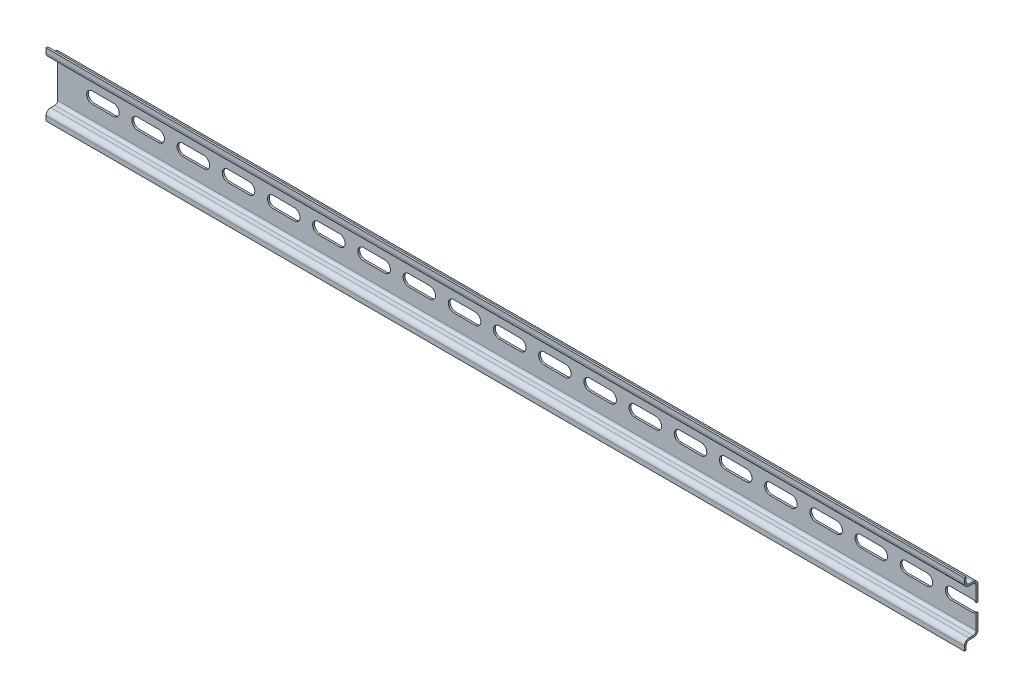
SolidWorks part; units mm, degrees
ref_plane "Front Plane" through (0, 0, 0) normal (0, 0, 1) x (1, 0, 0)
ref_plane "Top Plane" through (0, 0, 0) normal (0, 1, 0) x (1, 0, 0)
ref_plane "Right Plane" through (0, 0, 0) normal (1, 0, 0) x (0, 0, -1)
sketch "Sketch1" plane through (0, 0, 0) normal (1, 0, 0) x (0, 0, -1)
  line L0 (0, 0) -> (96.2341, 0) construction
  line L1 (0, 12.446) -> (0, -12.446)
  line L2 (0, -12.446) -> (-6.484, -12.446)
  line L3 (-6.484, -12.446) -> (-6.484, -17.526)
  line L4 (-6.484, -17.526) -> (-5.484, -17.526)
  line L5 (-5.484, -17.526) -> (-5.484, -13.462)
  line L6 (-5.484, -13.462) -> (1.016, -13.462)
  line L9 (1.016, -13.462) -> (1.016, 13.462)
  line L10 (-5.484, 17.526) -> (-5.484, 13.462)
  line L11 (-6.484, 17.526) -> (-5.484, 17.526)
  line L12 (-6.484, 12.446) -> (-6.484, 17.526)
  line L13 (0, 12.446) -> (-6.484, 12.446)
  line L14 (-5.484, 13.462) -> (1.016, 13.462)
  point P20 (1.016, 0)
  dimension "D1" = 96.2341
  dimension "D2" = 26.924
  dimension "D3" = 7.5
  dimension "D4" = 1
  dimension "D5" = 1.016
  dimension "D8" = 1.016
  dimension "D9" = 35.052
extrude "Boss-Extrude1" add sketch "Sketch1" along normal blind 1000
sketch "Sketch2" plane through (0, 0, -1.016) normal (0, 0, -1) x (-1, 0, 0)
  line L0 (-980.825, 0) -> (-969.175, 0) construction
  line L1 (-980.825, 3.175) -> (-969.175, 3.175)
  line L2 (-980.825, -3.175) -> (-969.175, -3.175)
  line L3 (-1000, -13.462) -> (-1000, 13.462) construction
  line L4 (-955.825, 0) -> (-944.175, 0) construction
  line L5 (-955.825, 3.175) -> (-944.175, 3.175)
  line L6 (-955.825, -3.175) -> (-944.175, -3.175)
  line L7 (-930.825, 0) -> (-919.175, 0) construction
  line L8 (-930.825, 3.175) -> (-919.175, 3.175)
  line L9 (-930.825, -3.175) -> (-919.175, -3.175)
  line L10 (-905.825, 0) -> (-894.175, 0) construction
  line L11 (-905.825, 3.175) -> (-894.175, 3.175)
  line L12 (-905.825, -3.175) -> (-894.175, -3.175)
  line L13 (-880.825, 0) -> (-869.175, 0) construction
  line L14 (-880.825, 3.175) -> (-869.175, 3.175)
  line L15 (-880.825, -3.175) -> (-869.175, -3.175)
  line L16 (-855.825, 0) -> (-844.175, 0) construction
  line L17 (-855.825, 3.175) -> (-844.175, 3.175)
  line L18 (-855.825, -3.175) -> (-844.175, -3.175)
  line L19 (-830.825, 0) -> (-819.175, 0) construction
  line L20 (-830.825, 3.175) -> (-819.175, 3.175)
  line L21 (-830.825, -3.175) -> (-819.175, -3.175)
  line L22 (-805.825, 0) -> (-794.175, 0) construction
  line L23 (-805.825, 3.175) -> (-794.175, 3.175)
  line L24 (-805.825, -3.175) -> (-794.175, -3.175)
  line L25 (-780.825, 0) -> (-769.175, 0) construction
  line L26 (-780.825, 3.175) -> (-769.175, 3.175)
  line L27 (-780.825, -3.175) -> (-769.175, -3.175)
  line L28 (-755.825, 0) -> (-744.175, 0) construction
  line L29 (-755.825, 3.175) -> (-744.175, 3.175)
  line L30 (-755.825, -3.175) -> (-744.175, -3.175)
  line L31 (-730.825, 0) -> (-719.175, 0) construction
  line L32 (-730.825, 3.175) -> (-719.175, 3.175)
  line L33 (-730.825, -3.175) -> (-719.175, -3.175)
  line L34 (-705.825, 0) -> (-694.175, 0) construction
  line L35 (-705.825, 3.175) -> (-694.175, 3.175)
  line L36 (-705.825, -3.175) -> (-694.175, -3.175)
  line L37 (-680.825, 0) -> (-669.175, 0) construction
  line L38 (-680.825, 3.175) -> (-669.175, 3.175)
  line L39 (-680.825, -3.175) -> (-669.175, -3.175)
  line L40 (-655.825, 0) -> (-644.175, 0) construction
  line L41 (-655.825, 3.175) -> (-644.175, 3.175)
  line L42 (-655.825, -3.175) -> (-644.175, -3.175)
  line L44 (-630.825, 0) -> (-619.175, 0) construction
  line L45 (-630.825, 3.175) -> (-619.175, 3.175)
  line L46 (-630.825, -3.175) -> (-619.175, -3.175)
  line L47 (-605.825, 0) -> (-594.175, 0) construction
  line L48 (-605.825, 3.175) -> (-594.175, 3.175)
  line L49 (-605.825, -3.175) -> (-594.175, -3.175)
  line L50 (-580.825, 0) -> (-569.175, 0) construction
  line L51 (-580.825, 3.175) -> (-569.175, 3.175)
  line L52 (-580.825, -3.175) -> (-569.175, -3.175)
  line L53 (-555.825, 0) -> (-544.175, 0) construction
  line L54 (-555.825, 3.175) -> (-544.175, 3.175)
  line L55 (-555.825, -3.175) -> (-544.175, -3.175)
  line L56 (-530.825, 0) -> (-519.175, 0) construction
  line L57 (-530.825, 3.175) -> (-519.175, 3.175)
  line L58 (-530.825, -3.175) -> (-519.175, -3.175)
  line L59 (-505.825, 0) -> (-494.175, 0) construction
  line L60 (-505.825, 3.175) -> (-494.175, 3.175)
  line L61 (-505.825, -3.175) -> (-494.175, -3.175)
  line L62 (-480.825, 0) -> (-469.175, 0) construction
  line L63 (-480.825, 3.175) -> (-469.175, 3.175)
  line L64 (-480.825, -3.175) -> (-469.175, -3.175)
  line L65 (-455.825, 0) -> (-444.175, 0) construction
  line L66 (-455.825, 3.175) -> (-444.175, 3.175)
  line L67 (-455.825, -3.175) -> (-444.175, -3.175)
  line L68 (-430.825, 0) -> (-419.175, 0) construction
  line L69 (-430.825, 3.175) -> (-419.175, 3.175)
  line L70 (-430.825, -3.175) -> (-419.175, -3.175)
  line L71 (-405.825, 0) -> (-394.175, 0) construction
  line L72 (-405.825, 3.175) -> (-394.175, 3.175)
  line L73 (-405.825, -3.175) -> (-394.175, -3.175)
  line L74 (-380.825, 0) -> (-369.175, 0) construction
  line L75 (-380.825, 3.175) -> (-369.175, 3.175)
  line L76 (-380.825, -3.175) -> (-369.175, -3.175)
  line L77 (-355.825, 0) -> (-344.175, 0) construction
  line L78 (-355.825, 3.175) -> (-344.175, 3.175)
  line L79 (-355.825, -3.175) -> (-344.175, -3.175)
  line L80 (-330.825, 0) -> (-319.175, 0) construction
  line L81 (-330.825, 3.175) -> (-319.175, 3.175)
  line L82 (-330.825, -3.175) -> (-319.175, -3.175)
  line L83 (-305.825, 0) -> (-294.175, 0) construction
  line L84 (-305.825, 3.175) -> (-294.175, 3.175)
  line L85 (-305.825, -3.175) -> (-294.175, -3.175)
  line L86 (-280.825, 0) -> (-269.175, 0) construction
  line L87 (-280.825, 3.175) -> (-269.175, 3.175)
  line L88 (-280.825, -3.175) -> (-269.175, -3.175)
  line L89 (-255.825, 0) -> (-244.175, 0) construction
  line L90 (-255.825, 3.175) -> (-244.175, 3.175)
  line L91 (-255.825, -3.175) -> (-244.175, -3.175)
  line L92 (-230.825, 0) -> (-219.175, 0) construction
  line L93 (-230.825, 3.175) -> (-219.175, 3.175)
  line L94 (-230.825, -3.175) -> (-219.175, -3.175)
  line L95 (-205.825, 0) -> (-194.175, 0) construction
  line L96 (-205.825, 3.175) -> (-194.175, 3.175)
  line L97 (-205.825, -3.175) -> (-194.175, -3.175)
  line L98 (-180.825, 0) -> (-169.175, 0) construction
  line L99 (-180.825, 3.175) -> (-169.175, 3.175)
  line L100 (-180.825, -3.175) -> (-169.175, -3.175)
  line L101 (-155.825, 0) -> (-144.175, 0) construction
  line L102 (-155.825, 3.175) -> (-144.175, 3.175)
  line L103 (-155.825, -3.175) -> (-144.175, -3.175)
  line L104 (-130.825, 0) -> (-119.175, 0) construction
  line L105 (-130.825, 3.175) -> (-119.175, 3.175)
  line L106 (-130.825, -3.175) -> (-119.175, -3.175)
  line L107 (-105.825, 0) -> (-94.175, 0) construction
  line L108 (-105.825, 3.175) -> (-94.175, 3.175)
  line L109 (-105.825, -3.175) -> (-94.175, -3.175)
  line L110 (-80.825, 0) -> (-69.175, 0) construction
  line L111 (-80.825, 3.175) -> (-69.175, 3.175)
  line L112 (-80.825, -3.175) -> (-69.175, -3.175)
  line L113 (-55.825, 0) -> (-44.175, 0) construction
  line L114 (-55.825, 3.175) -> (-44.175, 3.175)
  line L115 (-55.825, -3.175) -> (-44.175, -3.175)
  line L116 (-30.825, 0) -> (-19.175, 0) construction
  line L117 (-30.825, 3.175) -> (-19.175, 3.175)
  line L118 (-30.825, -3.175) -> (-19.175, -3.175)
  arc A0 (-980.825, 3.175) -> (-980.825, -3.175) centre (-980.825, 0) ccw
  arc A1 (-969.175, -3.175) -> (-969.175, 3.175) centre (-969.175, 0) ccw
  arc A2 (-955.825, 3.175) -> (-955.825, -3.175) centre (-955.825, 0) ccw
  arc A3 (-944.175, -3.175) -> (-944.175, 3.175) centre (-944.175, 0) ccw
  arc A4 (-930.825, 3.175) -> (-930.825, -3.175) centre (-930.825, 0) ccw
  arc A5 (-919.175, -3.175) -> (-919.175, 3.175) centre (-919.175, 0) ccw
  arc A6 (-905.825, 3.175) -> (-905.825, -3.175) centre (-905.825, 0) ccw
  arc A7 (-894.175, -3.175) -> (-894.175, 3.175) centre (-894.175, 0) ccw
  arc A8 (-880.825, 3.175) -> (-880.825, -3.175) centre (-880.825, 0) ccw
  arc A9 (-869.175, -3.175) -> (-869.175, 3.175) centre (-869.175, 0) ccw
  arc A10 (-855.825, 3.175) -> (-855.825, -3.175) centre (-855.825, 0) ccw
  arc A11 (-844.175, -3.175) -> (-844.175, 3.175) centre (-844.175, 0) ccw
  arc A12 (-830.825, 3.175) -> (-830.825, -3.175) centre (-830.825, 0) ccw
  arc A13 (-819.175, -3.175) -> (-819.175, 3.175) centre (-819.175, 0) ccw
  arc A14 (-805.825, 3.175) -> (-805.825, -3.175) centre (-805.825, 0) ccw
  arc A15 (-794.175, -3.175) -> (-794.175, 3.175) centre (-794.175, 0) ccw
  arc A16 (-780.825, 3.175) -> (-780.825, -3.175) centre (-780.825, 0) ccw
  arc A17 (-769.175, -3.175) -> (-769.175, 3.175) centre (-769.175, 0) ccw
  arc A18 (-755.825, 3.175) -> (-755.825, -3.175) centre (-755.825, 0) ccw
  arc A19 (-744.175, -3.175) -> (-744.175, 3.175) centre (-744.175, 0) ccw
  arc A20 (-730.825, 3.175) -> (-730.825, -3.175) centre (-730.825, 0) ccw
  arc A21 (-719.175, -3.175) -> (-719.175, 3.175) centre (-719.175, 0) ccw
  arc A22 (-705.825, 3.175) -> (-705.825, -3.175) centre (-705.825, 0) ccw
  arc A23 (-694.175, -3.175) -> (-694.175, 3.175) centre (-694.175, 0) ccw
  arc A24 (-680.825, 3.175) -> (-680.825, -3.175) centre (-680.825, 0) ccw
  arc A25 (-669.175, -3.175) -> (-669.175, 3.175) centre (-669.175, 0) ccw
  arc A26 (-655.825, 3.175) -> (-655.825, -3.175) centre (-655.825, 0) ccw
  arc A27 (-644.175, -3.175) -> (-644.175, 3.175) centre (-644.175, 0) ccw
  arc A28 (-630.825, 3.175) -> (-630.825, -3.175) centre (-630.825, 0) ccw
  arc A29 (-619.175, -3.175) -> (-619.175, 3.175) centre (-619.175, 0) ccw
  arc A30 (-605.825, 3.175) -> (-605.825, -3.175) centre (-605.825, 0) ccw
  arc A31 (-594.175, -3.175) -> (-594.175, 3.175) centre (-594.175, 0) ccw
  arc A32 (-580.825, 3.175) -> (-580.825, -3.175) centre (-580.825, 0) ccw
  arc A33 (-569.175, -3.175) -> (-569.175, 3.175) centre (-569.175, 0) ccw
  arc A34 (-555.825, 3.175) -> (-555.825, -3.175) centre (-555.825, 0) ccw
  arc A35 (-544.175, -3.175) -> (-544.175, 3.175) centre (-544.175, 0) ccw
  arc A36 (-530.825, 3.175) -> (-530.825, -3.175) centre (-530.825, 0) ccw
  arc A37 (-519.175, -3.175) -> (-519.175, 3.175) centre (-519.175, 0) ccw
  arc A38 (-505.825, 3.175) -> (-505.825, -3.175) centre (-505.825, 0) ccw
  arc A39 (-494.175, -3.175) -> (-494.175, 3.175) centre (-494.175, 0) ccw
  arc A40 (-480.825, 3.175) -> (-480.825, -3.175) centre (-480.825, 0) ccw
  arc A41 (-469.175, -3.175) -> (-469.175, 3.175) centre (-469.175, 0) ccw
  arc A42 (-455.825, 3.175) -> (-455.825, -3.175) centre (-455.825, 0) ccw
  arc A43 (-444.175, -3.175) -> (-444.175, 3.175) centre (-444.175, 0) ccw
  arc A44 (-430.825, 3.175) -> (-430.825, -3.175) centre (-430.825, 0) ccw
  arc A45 (-419.175, -3.175) -> (-419.175, 3.175) centre (-419.175, 0) ccw
  arc A46 (-405.825, 3.175) -> (-405.825, -3.175) centre (-405.825, 0) ccw
  arc A47 (-394.175, -3.175) -> (-394.175, 3.175) centre (-394.175, 0) ccw
  arc A48 (-380.825, 3.175) -> (-380.825, -3.175) centre (-380.825, 0) ccw
  arc A49 (-369.175, -3.175) -> (-369.175, 3.175) centre (-369.175, 0) ccw
  arc A50 (-355.825, 3.175) -> (-355.825, -3.175) centre (-355.825, 0) ccw
  arc A51 (-344.175, -3.175) -> (-344.175, 3.175) centre (-344.175, 0) ccw
  arc A52 (-330.825, 3.175) -> (-330.825, -3.175) centre (-330.825, 0) ccw
  arc A53 (-319.175, -3.175) -> (-319.175, 3.175) centre (-319.175, 0) ccw
  arc A54 (-305.825, 3.175) -> (-305.825, -3.175) centre (-305.825, 0) ccw
  arc A55 (-294.175, -3.175) -> (-294.175, 3.175) centre (-294.175, 0) ccw
  arc A56 (-280.825, 3.175) -> (-280.825, -3.175) centre (-280.825, 0) ccw
  arc A57 (-269.175, -3.175) -> (-269.175, 3.175) centre (-269.175, 0) ccw
  arc A58 (-255.825, 3.175) -> (-255.825, -3.175) centre (-255.825, 0) ccw
  arc A59 (-244.175, -3.175) -> (-244.175, 3.175) centre (-244.175, 0) ccw
  arc A60 (-230.825, 3.175) -> (-230.825, -3.175) centre (-230.825, 0) ccw
  arc A61 (-219.175, -3.175) -> (-219.175, 3.175) centre (-219.175, 0) ccw
  arc A62 (-205.825, 3.175) -> (-205.825, -3.175) centre (-205.825, 0) ccw
  arc A63 (-194.175, -3.175) -> (-194.175, 3.175) centre (-194.175, 0) ccw
  arc A64 (-180.825, 3.175) -> (-180.825, -3.175) centre (-180.825, 0) ccw
  arc A65 (-169.175, -3.175) -> (-169.175, 3.175) centre (-169.175, 0) ccw
  arc A66 (-155.825, 3.175) -> (-155.825, -3.175) centre (-155.825, 0) ccw
  arc A67 (-144.175, -3.175) -> (-144.175, 3.175) centre (-144.175, 0) ccw
  arc A68 (-130.825, 3.175) -> (-130.825, -3.175) centre (-130.825, 0) ccw
  arc A69 (-119.175, -3.175) -> (-119.175, 3.175) centre (-119.175, 0) ccw
  arc A70 (-105.825, 3.175) -> (-105.825, -3.175) centre (-105.825, 0) ccw
  arc A71 (-94.175, -3.175) -> (-94.175, 3.175) centre (-94.175, 0) ccw
  arc A72 (-80.825, 3.175) -> (-80.825, -3.175) centre (-80.825, 0) ccw
  arc A73 (-69.175, -3.175) -> (-69.175, 3.175) centre (-69.175, 0) ccw
  arc A74 (-55.825, 3.175) -> (-55.825, -3.175) centre (-55.825, 0) ccw
  arc A75 (-44.175, -3.175) -> (-44.175, 3.175) centre (-44.175, 0) ccw
  arc A76 (-30.825, 3.175) -> (-30.825, -3.175) centre (-30.825, 0) ccw
  arc A77 (-19.175, -3.175) -> (-19.175, 3.175) centre (-19.175, 0) ccw
  point P3 (-975, 0)
  point P8 (-984, 0)
  point P9 (-966, 0)
  point P15 (-950, 0)
  point P22 (-925, 0)
  point P29 (-900, 0)
  point P36 (-875, 0)
  point P43 (-850, 0)
  point P50 (-825, 0)
  point P57 (-800, 0)
  point P64 (-775, 0)
  point P71 (-750, 0)
  point P78 (-725, 0)
  point P85 (-700, 0)
  point P92 (-675, 0)
  point P99 (-650, 0)
  point P107 (-625, 0)
  point P114 (-600, 0)
  point P121 (-575, 0)
  point P128 (-550, 0)
  point P135 (-525, 0)
  point P142 (-500, 0)
  point P149 (-475, 0)
  point P156 (-450, 0)
  point P163 (-425, 0)
  point P170 (-400, 0)
  point P177 (-375, 0)
  point P184 (-350, 0)
  point P191 (-325, 0)
  point P198 (-300, 0)
  point P205 (-275, 0)
  point P212 (-250, 0)
  point P219 (-225, 0)
  point P226 (-200, 0)
  point P233 (-175, 0)
  point P240 (-150, 0)
  point P247 (-125, 0)
  point P254 (-100, 0)
  point P261 (-75, 0)
  point P268 (-50, 0)
  point P274 (-25, 0)
  dimension "D1" = 3.175
  dimension "D2" = 18
  dimension "D3" = 25
  dimension "D4" = 39
extrude "Cut-Extrude1" cut sketch "Sketch2" against normal through all
fillet "Fillet1" radius 2.54 4 edges at (500, -12.446, 6.484) (500, 12.446, 6.484) (500, -13.462, -1.016) (500, 13.462, -1.016)
fillet "Fillet2" radius 1.524 4 edges at (500, -13.462, 5.484) (500, 12.446, 0) (500, -12.446, 0) (500, 13.462, 5.484)
sketch "Sketch3" plane through (0, 0, -1.016) normal (0, 0, -1) x (-1, 0, 0)
  line L0 (-1000, -17.526) -> (0, -17.526) construction
  line L1 (-1000, 17.526) -> (-508, 17.526)
  line L2 (-1000, 17.526) -> (-1000, -17.526)
  line L3 (-1000, -17.526) -> (-508, -17.526)
  line L4 (-508, 17.526) -> (-508, -17.526)
  line L5 (0, -10.922) -> (0, 10.922) construction
  dimension "D1" = 508
extrude "Cut-Extrude2" cut sketch "Sketch3" against normal through all both and the other way through all
